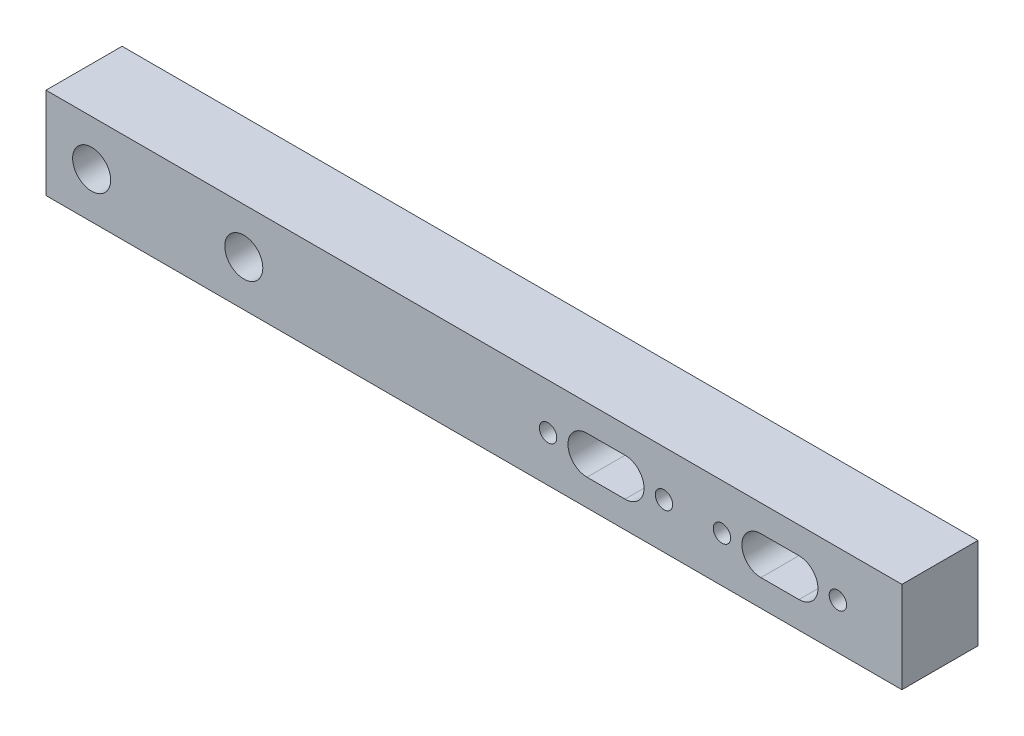
SolidWorks part; units mm, degrees
ref_plane "Front Plane" through (0, 0, 0) normal (0, 0, 1) x (1, 0, 0)
ref_plane "Top Plane" through (0, 0, 0) normal (0, 1, 0) x (1, 0, 0)
ref_plane "Right Plane" through (0, 0, 0) normal (1, 0, 0) x (0, 0, -1)
sketch "Sketch1" plane through (0, 0, 0) normal (0, 0, 1) x (1, 0, 0)
  line L0 (-84.4228, 73.1963) -> (-79.4228, 73.1963) construction
  line L1 (-155.5428, 79.1963) -> (-43.0227, 79.1963)
  line L2 (-155.5428, 79.1963) -> (-155.5428, 67.1963)
  line L3 (-155.5428, 67.1963) -> (-43.0227, 67.1963)
  line L4 (-43.0227, 79.1963) -> (-43.0227, 67.1963)
  line L5 (-84.4228, 75.6963) -> (-79.4228, 75.6963)
  line L6 (-84.4228, 70.6963) -> (-79.4228, 70.6963)
  line L7 (-89.5428, 73.1963) -> (-74.3028, 73.1963) construction
  line L8 (-66.6828, 73.1963) -> (-51.4428, 73.1963) construction
  line L9 (-61.5628, 73.1963) -> (-56.5628, 73.1963) construction
  line L10 (-61.5628, 75.6963) -> (-56.5628, 75.6963)
  line L11 (-61.5628, 70.6963) -> (-56.5628, 70.6963)
  circle A0 centre (-149.5428, 73.1963) radius 2.5
  circle A1 centre (-129.5428, 73.1963) radius 2.5
  circle A2 centre (-89.5428, 73.1963) radius 1.143
  circle A3 centre (-74.3028, 73.1963) radius 1.143
  circle A4 centre (-66.6828, 73.1963) radius 1.143
  circle A5 centre (-51.4428, 73.1963) radius 1.143
  arc A6 (-84.4228, 75.6963) -> (-84.4228, 70.6963) centre (-84.4228, 73.1963) ccw
  arc A7 (-79.4228, 70.6963) -> (-79.4228, 75.6963) centre (-79.4228, 73.1963) ccw
  arc A8 (-61.5628, 75.6963) -> (-61.5628, 70.6963) centre (-61.5628, 73.1963) ccw
  arc A9 (-56.5628, 70.6963) -> (-56.5628, 75.6963) centre (-56.5628, 73.1963) ccw
  point P16 (-81.9228, 73.1963)
  point P17 (-155.5428, 73.1963)
  point P19 (-43.0227, 73.1963)
  point P26 (-81.9228, 73.1963)
  point P28 (-59.0628, 73.1963)
  point P33 (0, 0)
  point P34 (-59.0628, 73.1963)
  dimension "D1" = 5
  dimension "D2" = 20
  dimension "D3" = 6
  dimension "D4" = 2.286
  dimension "D5" = 5
  dimension "D6" = 40
  dimension "D7" = 15.24
  dimension "D8" = 15.24
  dimension "D9" = 7.62
  dimension "D11" = 5
  dimension "D13" = 2.5
  dimension "D10" = 12
  dimension "D12" = 5
extrude "Boss-Extrude1" add sketch "Sketch1" along normal blind 10
